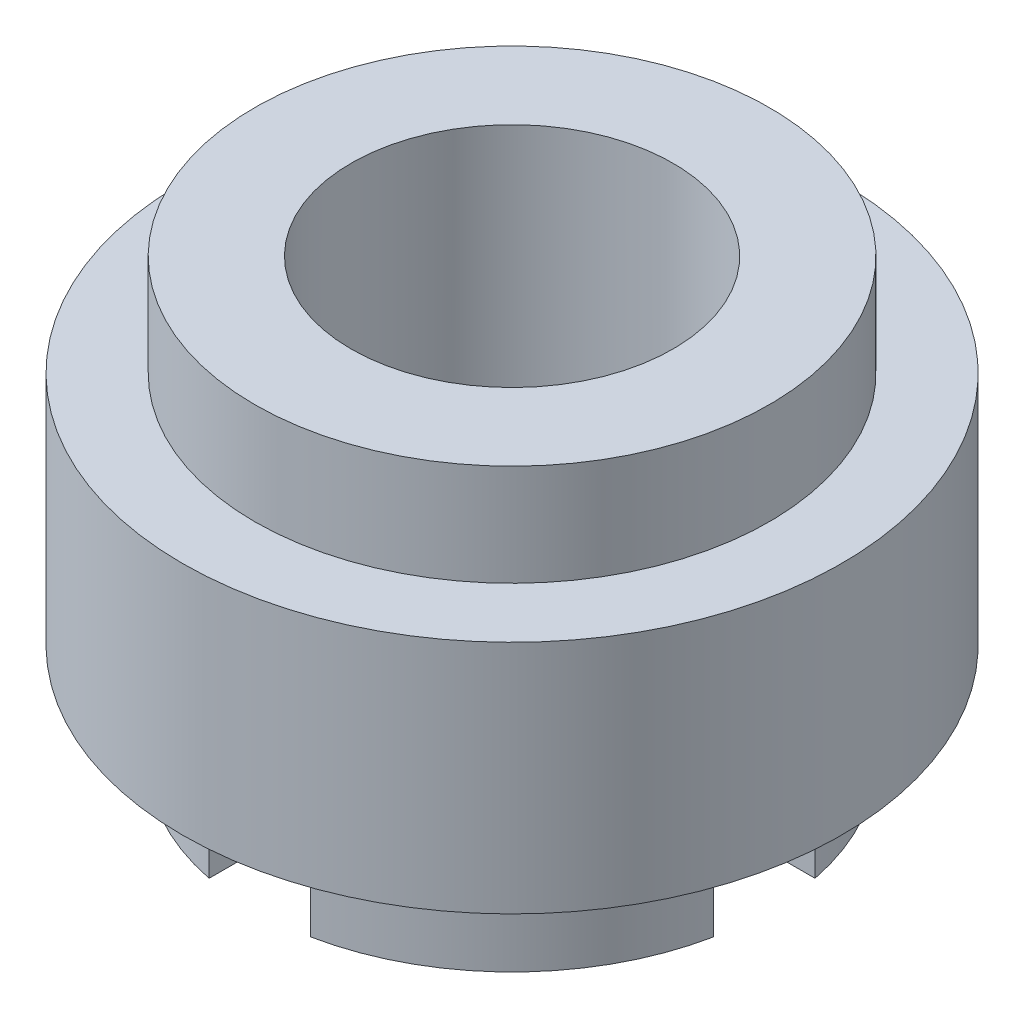
SolidWorks part; units mm, degrees
ref_plane "Front Plane" through (0, 0, 0) normal (0, 0, 1) x (1, 0, 0)
ref_plane "Top Plane" through (0, 0, 0) normal (0, 1, 0) x (1, 0, 0)
ref_plane "Right Plane" through (0, 0, 0) normal (1, 0, 0) x (0, 0, -1)
sketch "Sketch1" plane through (0, 0, 0) normal (0, 1, 0) x (1, 0, 0)
  circle A0 centre (0, 0) radius 6.5
  dimension "D1" = 13
extrude "Boss-Extrude1" add sketch "Sketch1" along normal blind 4.64
sketch "Sketch2" plane through (0, 4.64, 0) normal (0, 1, 0) x (1, 0, 0)
  circle A0 centre (0, 0) radius 5.075
  dimension "D1" = 10.15
extrude "Boss-Extrude2" add sketch "Sketch2" along normal blind 2
sketch "Sketch3" plane through (0, 0, 0) normal (0, -1, 0) x (1, 0, 0)
  circle A0 centre (0, 0) radius 5.075
  dimension "D1" = 10.15
extrude "Boss-Extrude3" add sketch "Sketch3" along normal blind 2
sketch "Sketch4" plane through (0, 6.64, 0) normal (0, 1, 0) x (1, 0, 0)
  circle A0 centre (0, 0) radius 3.175
  dimension "D1" = 6.35
extrude "Cut-Extrude1" cut sketch "Sketch4" against normal through all
sketch "Sketch5" plane through (0, 0, 0) normal (0, 0, 1) x (1, 0, 0)
  line L0 (0, 0) -> (-1, 0)
  line L1 (-1, 0) -> (-1, -2)
  line L2 (-1, -2) -> (1, -2)
  line L3 (1, -2) -> (1, 0)
  line L4 (1, 0) -> (0, 0)
  dimension "D1" = 1
  dimension "D2" = 2
  dimension "D3" = 2
extrude "Cut-Extrude2" cut sketch "Sketch5" along normal through all and the other way through all
sketch "Sketch6" plane through (0, 0, 0) normal (1, 0, 0) x (0, 0, -1)
  line L1 (0, 0) -> (-1, 0)
  line L2 (0, 0) -> (0, -2)
  line L3 (0, -2) -> (-1, -2)
  line L4 (-1, 0) -> (-1, -2)
  line L5 (0, 0) -> (1, 0)
  line L6 (0, 0) -> (0, -2)
  line L7 (0, -2) -> (1, -2)
  line L8 (1, 0) -> (1, -2)
  dimension "D1" = 1
  dimension "D2" = 2
  dimension "D3" = 1
extrude "Cut-Extrude3" cut sketch "Sketch6" against normal through all and the other way through all contours L8 L5 L2 L7 | L1 L4 L3 L2
